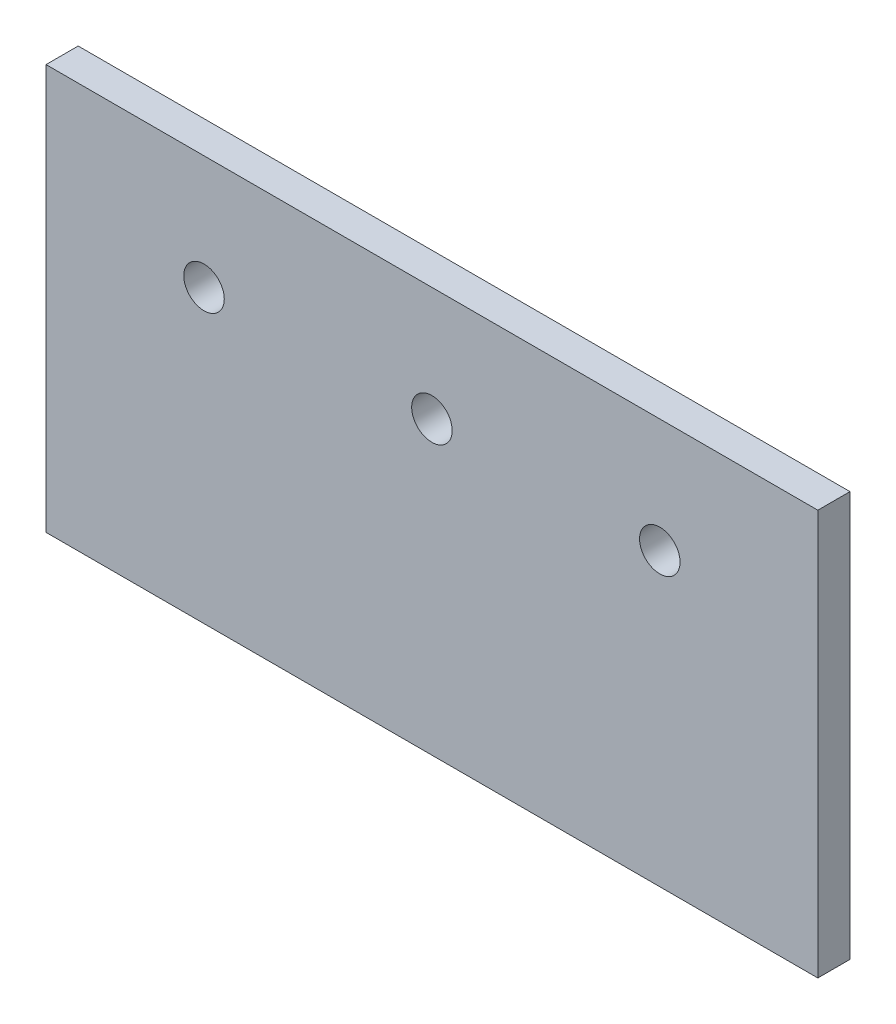
SolidWorks part; units mm, degrees
ref_plane "Front Plane" through (0, 0, 0) normal (0, 0, 1) x (1, 0, 0)
ref_plane "Top Plane" through (0, 0, 0) normal (0, 1, 0) x (1, 0, 0)
ref_plane "Right Plane" through (0, 0, 0) normal (1, 0, 0) x (0, 0, -1)
sketch "Sketch1" plane through (0, 0, 0) normal (0, 0, 1) x (1, 0, 0)
  line L1 (0, 0) -> (152.4, 0)
  line L2 (0, 0) -> (0, -80)
  line L3 (0, -80) -> (152.4, -80)
  line L4 (152.4, 0) -> (152.4, -80)
  circle A0 centre (76.2, -22.5) radius 4
  circle A1 centre (31.2, -22.5) radius 4
  circle A2 centre (121.2, -22.5) radius 4
  point P11 (0, 0)
  dimension "D3" = 76.2
  dimension "D5" = 45
  dimension "D6" = 8
  dimension "D7" = 45
  dimension "D4" = 22.5
  dimension "D1" = 80
  dimension "D2" = 152.4
extrude "Boss-Extrude1" add sketch "Sketch1" along normal blind 6.35
